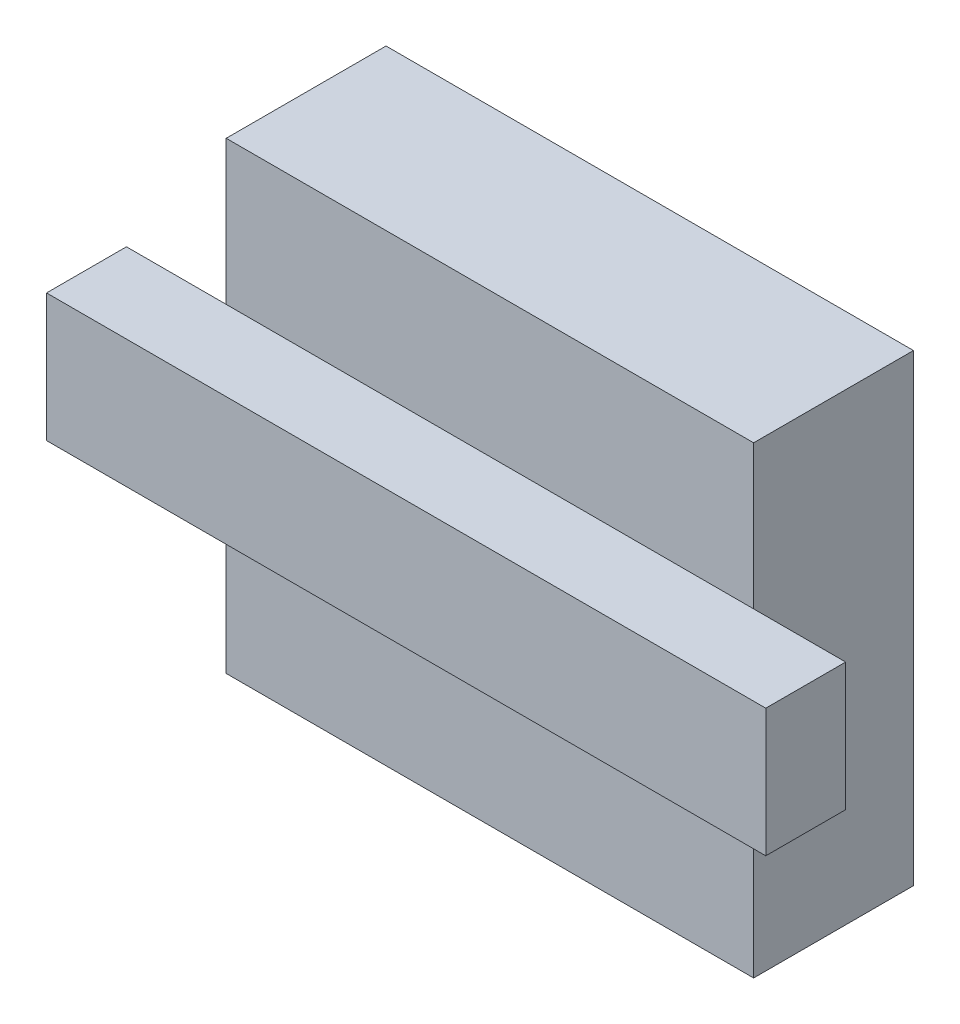
SolidWorks part; units mm, degrees
ref_plane "Front Plane" through (0, 0, 0) normal (0, 0, 1) x (1, 0, 0)
ref_plane "Top Plane" through (0, 0, 0) normal (0, 1, 0) x (1, 0, 0)
ref_plane "Right Plane" through (0, 0, 0) normal (1, 0, 0) x (0, 0, -1)
sketch "Sketch3" plane through (0, 0, 0) normal (0, 0, 1) x (1, 0, 0)
  line L1 (0, 0) -> (33, 0)
  line L2 (0, 0) -> (0, 29)
  line L3 (0, 29) -> (33, 29)
  line L4 (33, 0) -> (33, 29)
  dimension "D1" = 33
  dimension "D2" = 29
extrude "Boss-Extrude1" add sketch "Sketch3" along normal blind 10
sketch "Sketch4" plane through (0, 0, 10) normal (0, 0, 1) x (1, 0, 0)
  line L0 (16.2473, 18.6903) -> (16.2473, 22.9438)
  line L1 (-6.2414, 20) -> (38.7586, 20)
  line L2 (-6.2414, 20) -> (-6.2414, 12)
  line L3 (-6.2414, 12) -> (38.7586, 12)
  line L4 (38.7586, 20) -> (38.7586, 12)
  line L5 (16.2473, 29) -> (16.2473, 26.1444)
  line L6 (33, 29) -> (0, 29) construction
  line M7 (0, 29) -> (0, 0)
  line M9 (33, 0) -> (33, 29)
  dimension "D1" = 8
  dimension "D2" = 45
  dimension "D3" = 9
extrude "Boss-Extrude3" add sketch "Sketch4" along normal blind 5 contours L2 L3 L1 M7 | L3 L1 M7 M9 | L4 L1 L3 M9
